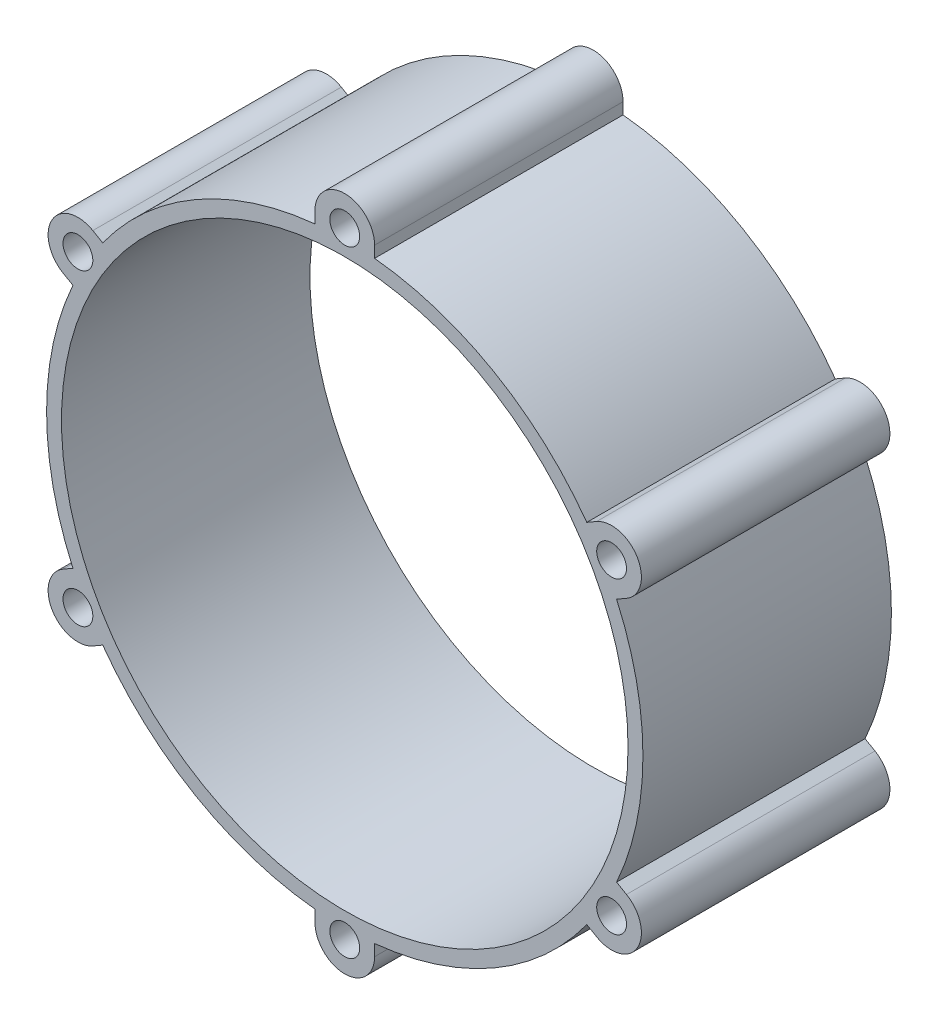
SolidWorks part; units mm, degrees
material "1060 Alloy"
ref_plane "Front Plane" through (0, 0, 0) normal (0, 0, 1) x (1, 0, 0)
ref_plane "Top Plane" through (0, 0, 0) normal (0, 1, 0) x (1, 0, 0)
ref_plane "Right Plane" through (0, 0, 0) normal (1, 0, 0) x (0, 0, -1)
sketch "Sketch1" plane through (0, 0, 0) normal (0, 0, 1) x (1, 0, 0)
  line L0 (6, 62) -> (6, 59.6992)
  line L1 (-6, 62) -> (-6, 59.6992)
  line L2 (56.6936, 25.8038) -> (54.7011, 24.6535)
  line L3 (50.6936, 36.1962) -> (48.7011, 35.0458)
  line L4 (50.6936, -36.1962) -> (48.7011, -35.0458)
  line L5 (56.6936, -25.8038) -> (54.7011, -24.6535)
  line L6 (-6, -62) -> (-6, -59.6992)
  line L7 (6, -62) -> (6, -59.6992)
  line L8 (-56.6936, -25.8038) -> (-54.7011, -24.6535)
  line L9 (-50.6936, -36.1962) -> (-48.7011, -35.0458)
  line L10 (-50.6936, 36.1962) -> (-48.7011, 35.0458)
  line L11 (-56.6936, 25.8038) -> (-54.7011, 24.6535)
  line L12 (0, 0) -> (6, 59.6992) construction
  circle A0 centre (0, 0) radius 60
  circle A1 centre (0, 0) radius 57
  arc A2 (6, 62) -> (-6, 62) centre (0, 62) ccw
  arc A3 (56.6936, 25.8038) -> (50.6936, 36.1962) centre (53.6936, 31) ccw
  arc A4 (50.6936, -36.1962) -> (56.6936, -25.8038) centre (53.6936, -31) ccw
  arc A5 (-6, -62) -> (6, -62) centre (0, -62) ccw
  arc A6 (-56.6936, -25.8038) -> (-50.6936, -36.1962) centre (-53.6936, -31) ccw
  arc A7 (-50.6936, 36.1962) -> (-56.6936, 25.8038) centre (-53.6936, 31) ccw
  dimension "D1" = 120
  dimension "D2" = 6
  dimension "D4" = 3
  dimension "D3" = 62
  dimension "D5" = 6
extrude "Boss-Extrude1" add sketch "Sketch1" along normal mid plane 50
sketch "Sketch3" plane through (0, 0, -25) normal (0, 0, -1) x (-1, 0, 0)
  circle A0 centre (0, 62) radius 3
  dimension "D1" = 6
extrude "Cut-Extrude1" cut sketch "Sketch3" against normal through all
pattern_circular "CirPattern1" count 6 over 360 about axis through (0, 0, 0) along (0, 0, 1) of "Cut-Extrude1"
